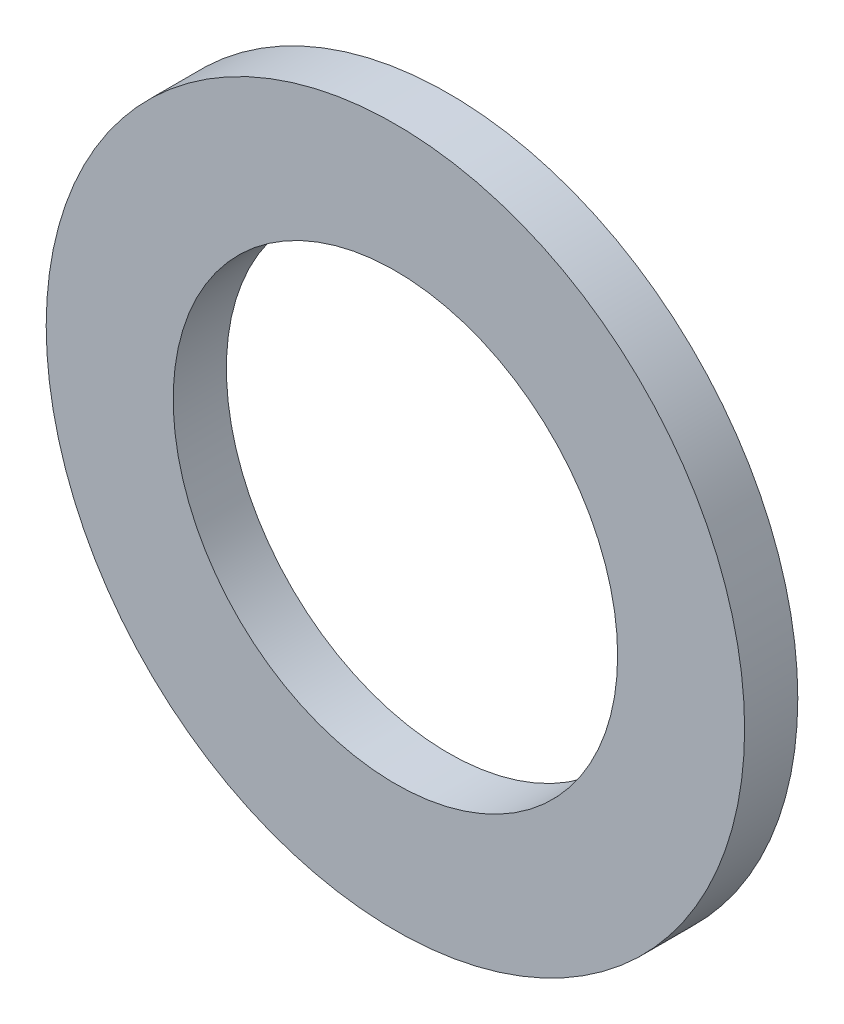
SolidWorks part; units mm, degrees
ref_plane "Front Plane" through (0, 0, 0) normal (0, 0, 1) x (1, 0, 0)
ref_plane "Top Plane" through (0, 0, 0) normal (0, 1, 0) x (1, 0, 0)
ref_plane "Right Plane" through (0, 0, 0) normal (1, 0, 0) x (0, 0, -1)
sketch "Sketch1" plane through (0, 0, 0) normal (0, 0, 1) x (1, 0, 0)
  circle A0 centre (0, 0) radius 14
  dimension "D1" = 28
extrude "Extrude-Thin2" add sketch "Sketch1" along normal blind 3.35 thin
